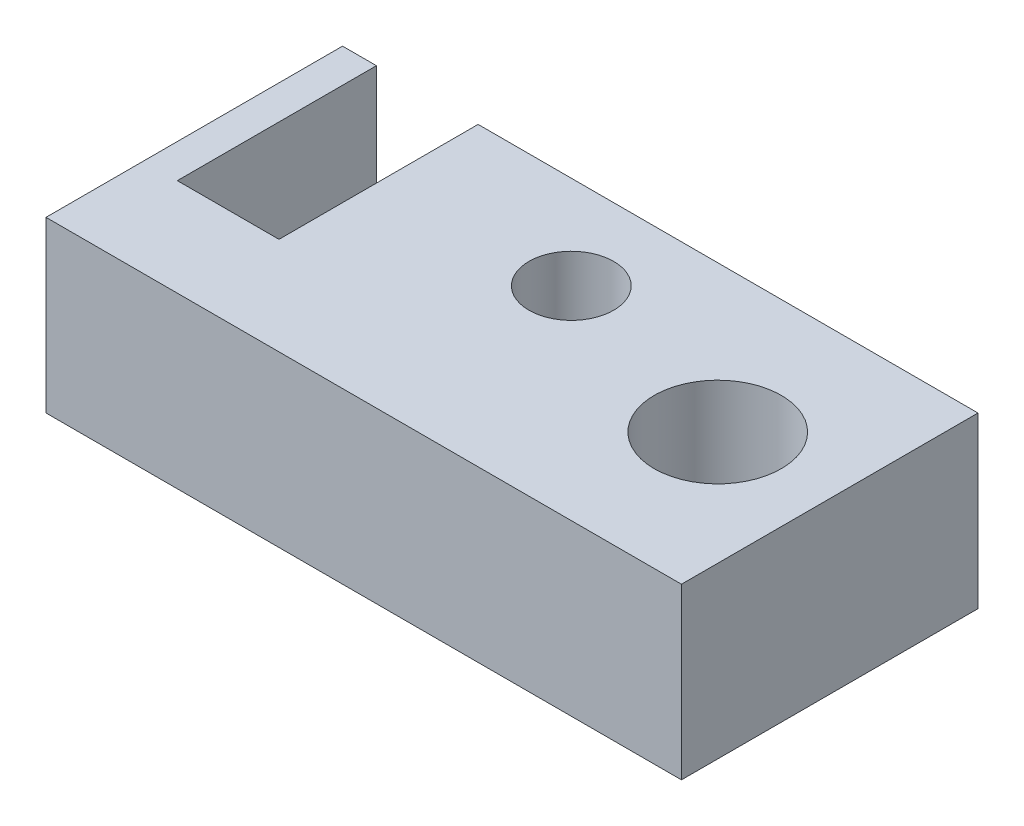
SolidWorks part; units mm, degrees
ref_plane "Front Plane" through (0, 0, 0) normal (0, 0, 1) x (1, 0, 0)
ref_plane "Top Plane" through (0, 0, 0) normal (0, 1, 0) x (1, 0, 0)
ref_plane "Right Plane" through (0, 0, 0) normal (1, 0, 0) x (0, 0, -1)
sketch "Sketch1" plane through (0, 0, 0) normal (0, 1, 0) x (1, 0, 0)
  line L1 (-37.5, -17.5) -> (37.5, -17.5)
  line L2 (-37.5, -17.5) -> (-37.5, 17.5)
  line L3 (-37.5, 17.5) -> (37.5, 17.5)
  line L4 (37.5, -17.5) -> (37.5, 17.5)
  line L5 (-37.5, -17.5) -> (37.5, 17.5) construction
  line L6 (-37.5, 17.5) -> (37.5, -17.5) construction
  circle A0 centre (24.0874, 0.1969) radius 7.5
  circle A2 centre (-27.5, 0.1969) radius 4
  point P0 (0, 0)
  dimension "D3" = 8
  dimension "D4" = 10
  dimension "D5" = 15
  dimension "D1" = 75
  dimension "D2" = 35
extrude "Boss-Extrude1" add sketch "Sketch1" along normal blind 20
sketch "Sketch2" plane through (0, 20, 0) normal (0, 1, 0) x (1, 0, 0)
  line L0 (37.5, 17.5) -> (-37.5, 17.5) construction
  line L1 (-33.5, 17.5) -> (-21.5, 17.5)
  line L2 (-33.5, 17.5) -> (-33.5, -6)
  line L3 (-33.5, -6) -> (-21.5, -6)
  line L4 (-21.5, 17.5) -> (-21.5, -6)
  circle A0 centre (-27.5, 0.1969) radius 4 construction
  dimension "D1" = 23.5
  dimension "D2" = 12
  dimension "D3" = 6
extrude "Cut-Extrude1" cut sketch "Sketch2" against normal blind 15
sketch "Sketch3" plane through (0, 20, 0) normal (0, 1, 0) x (1, 0, 0)
  line L0 (37.5, 17.5) -> (-21.5, 17.5) construction
  line L1 (37.5, -17.5) -> (37.5, 17.5) construction
  circle A0 centre (0.5, 6.5) radius 5
  dimension "D1" = 10
  dimension "D2" = 11
  dimension "D3" = 37
extrude "Cut-Extrude2" cut sketch "Sketch3" against normal through all
